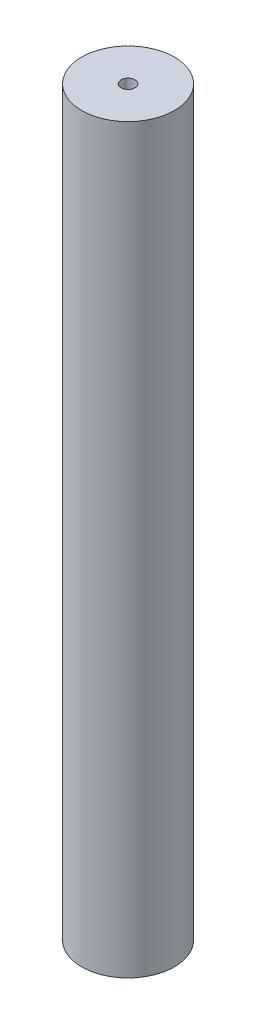
SolidWorks part; units mm, degrees
ref_plane "Front Plane" through (0, 0, 0) normal (0, 0, 1) x (1, 0, 0)
ref_plane "Top Plane" through (0, 0, 0) normal (0, 1, 0) x (1, 0, 0)
ref_plane "Right Plane" through (0, 0, 0) normal (1, 0, 0) x (0, 0, -1)
sketch "Sketch1" plane through (0, 0, 0) normal (0, 0, 1) x (1, 0, 0)
  line L0 (0, -77.0806) -> (0, 87.0349) construction
  line L1 (0, 0) -> (3, 0)
  line L2 (3, 0) -> (3, 76)
  line L5 (3.6027, 78) -> (5, 78)
  line L6 (5, 78) -> (5, -2)
  line L7 (5, -2) -> (0, -2)
  line L8 (0, -2) -> (0, 0)
  line L9 (3.6027, 78) -> (0.75, 78)
  line L10 (0.75, 78) -> (0.75, 76)
  line L11 (0.75, 76) -> (3, 76)
  point P1 (0, 0)
  point P3 (-0.2277, 87.0349)
  point P4 (0, 0)
  point P15 (0, 0)
  dimension "D1" = 80
  dimension "D2" = 2
  dimension "D3" = 2
  dimension "D4" = 2
  dimension "D5" = 6
  dimension "D6" = 1.5
revolve "Revolve1" add sketch "Sketch1" angle 360 about L0
ref_plane "Plane1" through (0, 48, 0) normal (0, 1, 0) x (1, 0, 0)
